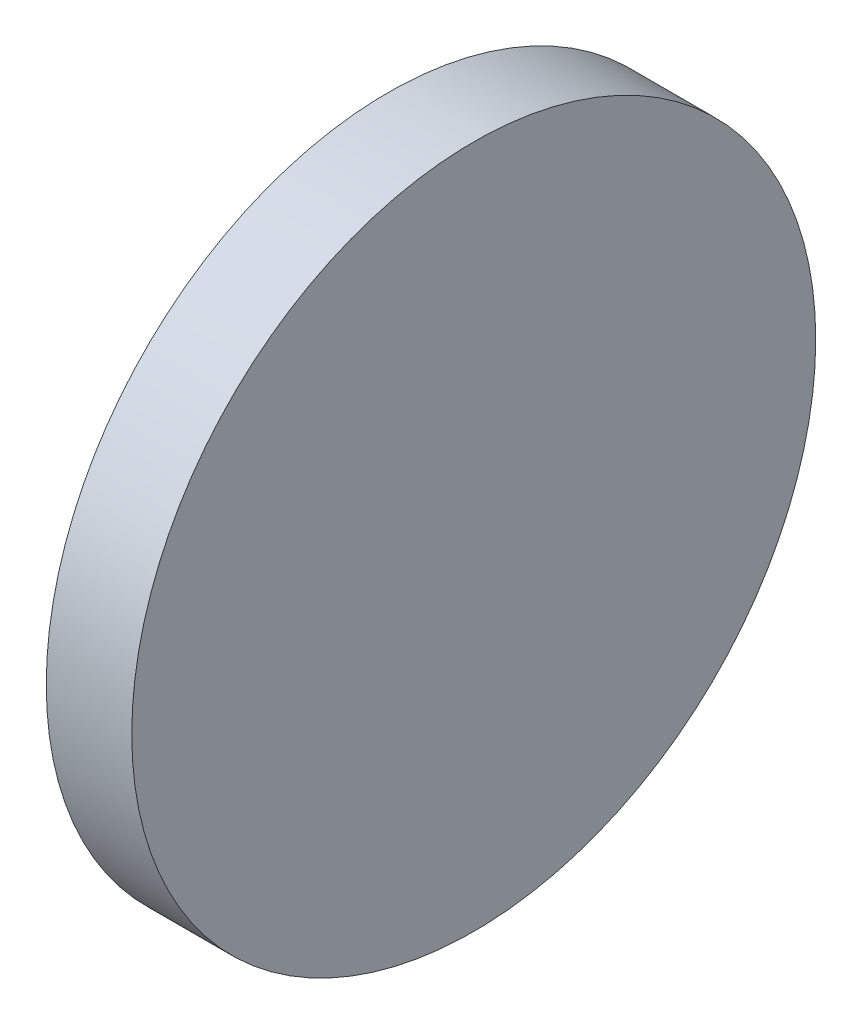
SolidWorks part; units mm, degrees
ref_plane "Front Plane" through (0, 0, 0) normal (0, 0, 1) x (1, 0, 0)
ref_plane "Top Plane" through (0, 0, 0) normal (0, 1, 0) x (1, 0, 0)
ref_plane "Right Plane" through (0, 0, 0) normal (1, 0, 0) x (0, 0, -1)
sketch "Sketch1" plane through (0, 0, 0) normal (1, 0, 0) x (0, 0, -1)
  circle A0 centre (0, 0) radius 25.4
  dimension "D1" = 50.8
extrude "Boss-Extrude1" add sketch "Sketch1" along normal blind 6.35
